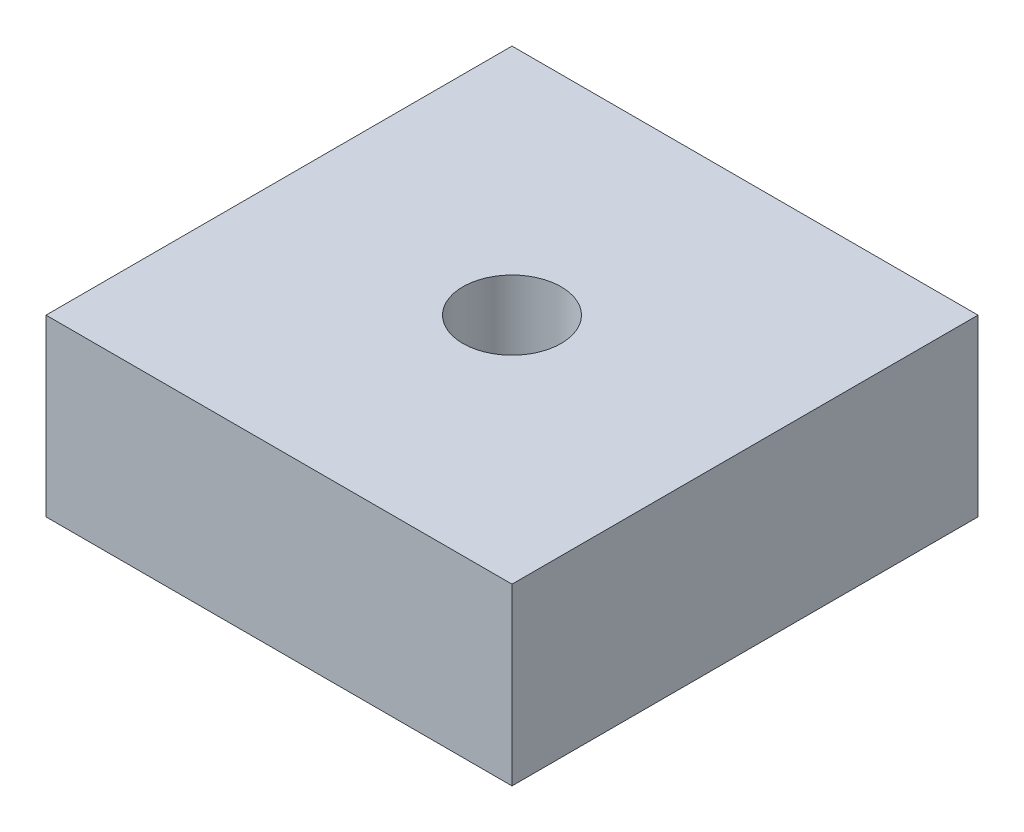
SolidWorks part; units mm, degrees
ref_plane "Front" through (0, 0, 0) normal (0, 0, 1) x (1, 0, 0)
ref_plane "Top" through (0, 0, 0) normal (0, 1, 0) x (1, 0, 0)
ref_plane "Right" through (0, 0, 0) normal (1, 0, 0) x (0, 0, -1)
sketch "Sketch1" plane through (0, 0, 0) normal (0, 0, 1) x (1, 0, 0)
  line L1 (0, 0) -> (50.8, 0)
  line L2 (0, 0) -> (0, 19.05)
  line L3 (0, 19.05) -> (50.8, 19.05)
  line L4 (50.8, 0) -> (50.8, 19.05)
  dimension "D1" = 19.05
  dimension "D2" = 50.8
extrude "Extrude1" add sketch "Sketch1" along normal blind 50.8
hole_wizard "1/2-13 Tapped Hole1" positions "Sketch3" profile "Sketch2" tap size "1/2-13" standard "Ansi Inch"
sketch "Sketch3" plane through (0, 19.05, 0) normal (0, 1, 0) x (-1, 0, 0)
  line L0 (0, 0) -> (-50.8, 50.8) construction
  line L1 (-50.8, 0) -> (0, 0) construction
  line L2 (0, 50.8) -> (0, 0) construction
  point P0 (-25.4, 25.4)
  dimension "D1" = 25.4
  dimension "D2" = 25.4
cosmetic thread "Cosmetic Thread1"
sketch "Sketch2" plane through (25.4, 19.05, 25.4) normal (1, 0, 0) x (0, 0, 1)
  line L0 (0, 0) -> (0, 19.05)
  line L1 (0, 19.05) -> (5.3581, 19.05)
  line L2 (5.3581, 19.05) -> (5.3581, 0)
  line L5 (5.3581, 0) -> (0, 0)
  line L11 (0, -6.35) -> (0, 107.95) construction
  dimension "Thru Tap Drill Dia." = 10.7163
  dimension "Thru Tap Drill Depth" = 19.05
